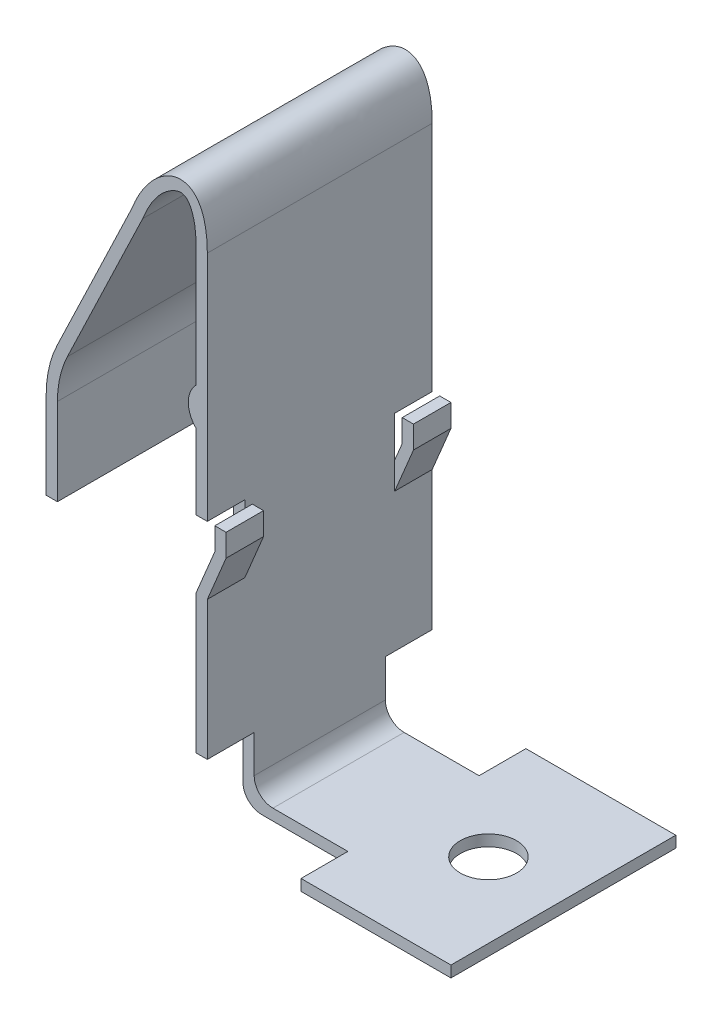
SolidWorks part; units mm, degrees
ref_plane "Front Plane" through (0, 0, 0) normal (0, 0, 1) x (1, 0, 0)
ref_plane "Top Plane" through (0, 0, 0) normal (0, 1, 0) x (1, 0, 0)
ref_plane "Right Plane" through (0, 0, 0) normal (1, 0, 0) x (0, 0, -1)
sketch "Sketch1" plane through (0, 0, 0) normal (0, 1, 0) x (1, 0, 0)
  line L0 (0, 3) -> (0, -3) construction
  line L1 (-2, 0) -> (2, 0) construction
  line L2 (-2, 3) -> (2, 3)
  line L3 (2, 3) -> (2, -3)
  line L4 (2, -3) -> (-2, -3)
  line L5 (-2, -3) -> (-2, -1.75)
  line L6 (-2, 1.75) -> (-4.5, 1.75)
  line L7 (-4.5, 1.75) -> (-4.5, -1.75)
  line L8 (-4.5, -1.75) -> (-2, -1.75)
  line L9 (-2, 1.75) -> (-2, 3)
  point P4 (0, 0)
  point P8 (0, 0)
  dimension "D1" = 6
  dimension "D2" = 4
  dimension "D3" = 1.75
  dimension "D4" = 1.75
  dimension "D5" = 2.5
  dimension "D6" = 4
extrude "Boss-Extrude1" add sketch "Sketch1" along normal blind 0.3
sketch "Sketch2" plane through (0, 0, 1.75) normal (0, 0, 1) x (1, 0, 0)
  line L0 (-4.5, 0) -> (-4.8, 0)
  line L1 (-4.5, 0) -> (-4.5, 13.5)
  line L2 (-4.8, 0) -> (-4.8, 13.5)
  line L3 (-4.8, 13.5) -> (-4.5, 13.5)
  dimension "D1" = 0.3
  dimension "D2" = 13.5
  dimension "D3" = 13.5
extrude "Boss-Extrude2" add sketch "Sketch2" against normal blind 3 and the other way blind 3 from offset 1.75 offset against normal yes
sketch "Sketch3" plane through (0, 0, 1.75) normal (0, 0, 1) x (1, 0, 0)
  line L0 (-4.5, 0) -> (-4.5, 13.5) construction
  line L1 (-6.5, 13.5546) -> (-8.5054, 9.3693)
  line L2 (-8.8, 8.0729) -> (-8.8, 5.7546)
  line L6 (-6.2242, 13.436) -> (-8.2349, 9.2397)
  line L7 (-8.5, 8.0729) -> (-8.5, 5.7546)
  line L8 (-4.8, 13.5) -> (-4.8, 0) construction
  line L9 (-4.8, 13.5) -> (-4.5, 13.5)
  line L10 (-8.8, 5.7546) -> (-8.5, 5.7546)
  arc A0 (-8.8, 8.0729) -> (-8.5054, 9.3693) centre (-5.8, 8.0729) cw
  arc A1 (-8.5, 8.0729) -> (-8.2349, 9.2397) centre (-5.8, 8.0729) cw
  spline S0 degree 3 poles (-4.5, 13.5) (-4.5, 15.508) (-5.9263, 15.0551) (-6.5, 13.5546) knots 0 0 0 0 1 1 1 1
  spline S1 degree 1 poles (-4.8, 13.5) (-6.2242, 13.436) knots 0 0 1 1 construction
  spline S2 degree 3 poles (-4.8, 13.5) (-4.8, 13.6065) (-4.8105, 13.8343) (-4.8656, 14.1683) (-4.9856, 14.4412) (-5.114, 14.5372) (-5.2747, 14.5715) (-5.6452, 14.388) (-6.0036, 13.9245) (-6.1627, 13.5968) (-6.2242, 13.436) knots 0 0 0 0 0.062659 0.125318 0.250636 0.375954 0.501272 0.751908 0.877225 1.002543 1.002543 1.002543 1.002543
  point P0 (-6.5, 13.5546)
  point P11 (-8.8, 8.7546)
  dimension "D4" = 3
  dimension "D1" = 2
  dimension "D2" = 4.8
  dimension "D3" = 3
  dimension "D6" = 4
  dimension "D5" = 0.3
extrude "Boss-Extrude3" add sketch "Sketch3" against normal blind 3 and the other way blind 3 from offset 1.75 offset against normal yes
sketch "Sketch4" plane through (0, 0.3, 0) normal (0, 1, 0) x (1, 0, 0)
  circle A0 centre (0, 0) radius 0.75
  dimension "D1" = 1.5
extrude "Cut-Extrude1" cut sketch "Sketch4" against normal up to next
sketch "Sketch6" plane through (-4.5, 0, 0) normal (1, 0, 0) x (0, 0, -1)
  line L2 (-1.75, 1.8) -> (-1.75, 0.3)
  line L3 (-3, 0.3) -> (3, 0.3) construction
  line L5 (1.75, 0.3) -> (1.75, 1.8)
  line L6 (-1.75, 1.8) -> (-3, 1.8)
  line L7 (-3, 0) -> (-3, 13.5) construction
  line L8 (-3, 1.8) -> (-3, 0)
  line L9 (-3, 0) -> (-1.75, 0)
  line L10 (-1.75, 0) -> (-1.75, 0.3)
  line L11 (1.75, 1.8) -> (3, 1.8)
  line L12 (3, 0) -> (3, 13.5) construction
  line L13 (3, 1.8) -> (3, 0)
  line L14 (3, 0) -> (1.75, 0)
  line L15 (1.75, 0) -> (1.75, 1.8)
  point P3 (0, 1.8)
  line M2 (-1.75, 0) -> (-1.75, 0.3)
  line M4 (1.75, 0.3) -> (1.75, 0)
  line M5 (1.75, 0) -> (3, 0)
  line M6 (3, 0) -> (3, 13.5)
  line M8 (-3, 13.5) -> (-3, 0)
  line M9 (-3, 0) -> (-1.75, 0)
  dimension "D1" = 3.5
extrude "Cut-Extrude2" cut sketch "Sketch6" against normal up to next contours L11 L5 M4 M5 M6 | L2 L6 M8 M9 M2
sketch "Sketch7" plane through (0, 0, 3) normal (0, 0, 1) x (1, 0, 0)
  line L0 (-4.8, 5.5) -> (-4.5, 5.5)
  line L1 (-4.8, 13.5) -> (-4.8, 1.8) construction
  line L2 (-4.5, 1.8) -> (-4.5, 13.5) construction
  line L3 (-4.8, 1.8) -> (-4.5, 1.8) construction
  line L4 (-4.8, 7.3) -> (-4.5, 7.3)
  line L5 (-4.5, 7.3) -> (-4.5, 5.5)
  line L6 (-4.8, 7.3) -> (-4.8, 5.5)
  dimension "D1" = 3.7
  dimension "D2" = 1.8
extrude "Cut-Extrude3" cut sketch "Sketch7" against normal blind 1
mirror "Mirror1" about plane through (0, 0, 0) normal (0, 0, 1) of "Cut-Extrude3"
sketch "Sketch8" plane through (0, 0, 3) normal (0, 0, 1) x (1, 0, 0)
  line L0 (-4.5, 5.5) -> (-4, 6.7)
  line L2 (-4.8, 5.5) -> (-4.3, 6.7)
  line L4 (-4.8, 5.5) -> (-4.5, 5.5)
  line L6 (-4.5, 5.5) -> (-4.5, 7.3) construction
  line L14 (-4.3, 7.3) -> (-4.3, 6.7)
  line L15 (-4, 6.7) -> (-4, 7.3)
  line L16 (-4, 7.3) -> (-4.3, 7.3)
  dimension "D1" = 0.5
extrude "Boss-Extrude4" add sketch "Sketch8" against normal blind 1
mirror "Mirror2" about plane through (0, 0, 0) normal (0, 0, 1) of "Boss-Extrude4"
sketch "Sketch9" plane through (0, 0, 3) normal (0, 0, 1) x (1, 0, 0)
  line L0 (-5.651, 9.8) -> (-4.8, 9.8) construction
  line L1 (-4.8, 10.3) -> (-4.8, 9.3)
  line L2 (-4.8, 13.5) -> (-4.8, 7.3) construction
  arc A0 (-4.8, 10.3) -> (-4.8, 9.3) centre (-4.3, 9.8) ccw
  point P9 (-4.8, 9.8)
  dimension "D1" = 9.5
  dimension "D2" = 1
extrude "Boss-Extrude5" add sketch "Sketch9" against normal blind 1
mirror "Mirror4" about plane through (0, 0, 0) normal (0, 0, 1) of "Boss-Extrude5"
fillet "Fillet1" radius 0.5 2 edges at (-4.8, 0, 0) (-4.5, 0.3, 0)
